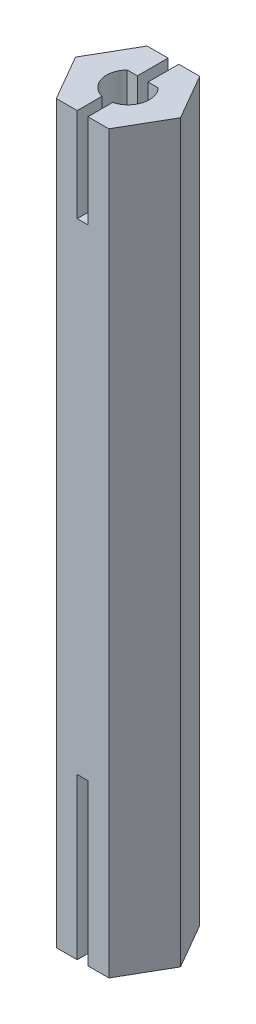
SolidWorks part; units mm, degrees
ref_plane "前视基准面" through (0, 0, 0) normal (0, 0, 1) x (1, 0, 0)
ref_plane "上视基准面" through (0, 0, 0) normal (0, 1, 0) x (1, 0, 0)
ref_plane "右视基准面" through (0, 0, 0) normal (1, 0, 0) x (0, 0, -1)
sketch "草图2" plane through (0, 0, 0) normal (0, 1, 0) x (1, 0, 0)
  line L1 (3.926, 0) -> (1.963, 3.4)
  line L2 (1.963, 3.4) -> (-1.963, 3.4)
  line L3 (-1.963, 3.4) -> (-3.926, 0)
  line L4 (-3.926, 0) -> (-1.963, -3.4)
  line L5 (-1.963, -3.4) -> (1.963, -3.4)
  line L6 (1.963, -3.4) -> (3.926, 0)
  circle A0 centre (0, 0) radius 3.4 construction
  dimension "D1" = 6.8
extrude "凸台-拉伸1" add sketch "草图2" along normal blind 55
sketch "草图3" plane through (0, 55, 0) normal (0, 1, 0) x (1, 0, 0)
  line L0 (-1.1619, 1.1) -> (1.1619, 1.1)
  circle A0 centre (0, 0) radius 1.6
  dimension "D1" = 3.2
  dimension "D2" = 1.1
extrude "切除-拉伸1" cut sketch "草图3" against normal blind 7 contours L0 A0
sketch "草图4" plane through (0, 0, 0) normal (0, -1, 0) x (1, 0, 0)
  line L1 (-1.5011, -2.6) -> (1.5011, -2.6)
  line L2 (1.5011, -2.6) -> (3.0022, 0)
  line L3 (3.0022, 0) -> (1.5011, 2.6)
  line L4 (1.5011, 2.6) -> (-1.5011, 2.6)
  line L5 (-1.5011, 2.6) -> (-3.0022, 0)
  line L6 (-3.0022, 0) -> (-1.5011, -2.6)
  circle A0 centre (0, 0) radius 2.6 construction
  dimension "D1" = 5.2
extrude "切除-拉伸2" cut sketch "草图4" against normal blind 12
sketch "草图5" plane through (0, 12, 0) normal (0, -1, 0) x (1, 0, 0)
  circle A0 centre (0, 0) radius 1.9
  dimension "D1" = 3.8
extrude "切除-拉伸3" cut sketch "草图5" against normal offset from surface (35 mm away) 1 up to face at (0, 48, 0.25)
sketch "草图6" plane through (0, 55, 0) normal (0, 1, 0) x (1, 0, 0)
  line L0 (1.963, 3.4) -> (-1.963, 3.4) construction
  line L1 (-0.4, 3.4) -> (0.4, 3.4)
  line L2 (-0.4, 3.4) -> (-0.4, -3.4)
  line L3 (-0.4, -3.4) -> (0.4, -3.4)
  line L4 (0.4, 3.4) -> (0.4, -3.4)
  line L5 (-1.963, -3.4) -> (1.963, -3.4) construction
  line L6 (0, 3.4) -> (0, 1.1) construction
  line L7 (-1.1619, 1.1) -> (1.1619, 1.1) construction
  dimension "D1" = 0.8
extrude "切除-拉伸4" cut sketch "草图6" against normal up to surface (7 mm away) up to face at (0, 48, 0.25)
sketch "草图7" plane through (0, 0, 0) normal (0, -1, 0) x (1, 0, 0)
  line L0 (1.963, -3.4) -> (-1.963, -3.4) construction
  line L1 (-0.4, 3.4) -> (0.4, 3.4)
  line L2 (-0.4, 3.4) -> (-0.4, -3.4)
  line L3 (-0.4, -3.4) -> (0.4, -3.4)
  line L4 (0.4, 3.4) -> (0.4, -3.4)
  line L5 (-1.963, 3.4) -> (1.963, 3.4) construction
  line L6 (0, 3.4) -> (0, 0) construction
  dimension "D1" = 0.8
extrude "切除-拉伸5" cut sketch "草图7" against normal up to surface (12 mm away) up to face at (0, 12, -1.9)
